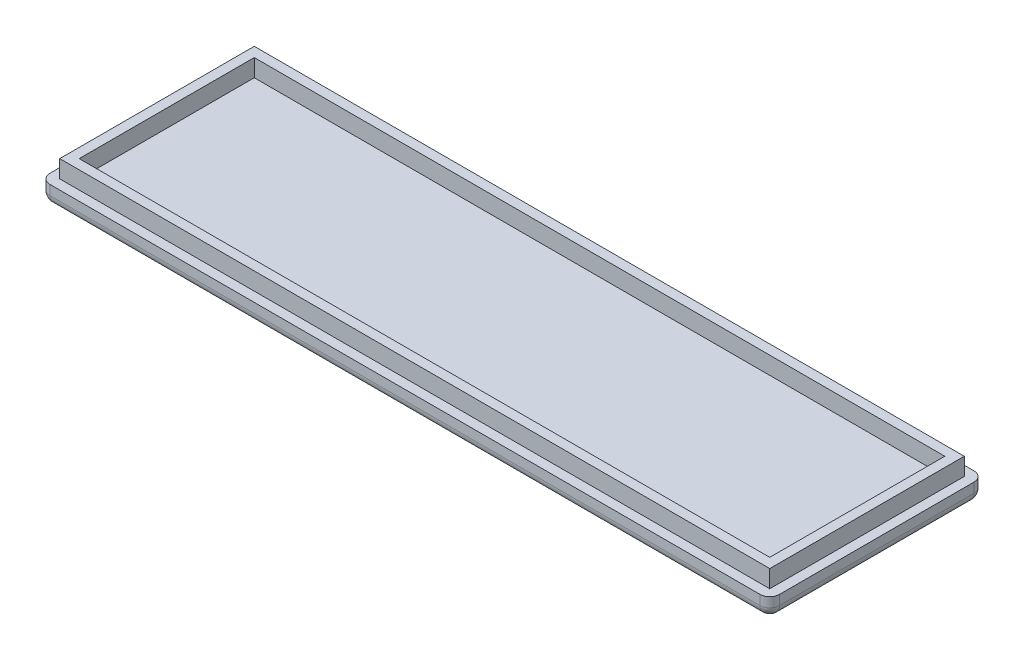
SolidWorks part; units mm, degrees
ref_plane "Front Plane" through (0, 0, 0) normal (0, 0, 1) x (1, 0, 0)
ref_plane "Top Plane" through (0, 0, 0) normal (0, 1, 0) x (1, 0, 0)
ref_plane "Right Plane" through (0, 0, 0) normal (1, 0, 0) x (0, 0, -1)
sketch "Sketch1" plane through (0, 0, 0) normal (0, 1, 0) x (1, 0, 0)
  line L1 (-37.5, -11) -> (37.5, -11)
  line L2 (-37.5, -11) -> (-37.5, 11)
  line L3 (-37.5, 11) -> (37.5, 11)
  line L4 (37.5, -11) -> (37.5, 11)
  line L5 (-37.5, -11) -> (37.5, 11) construction
  line L6 (-37.5, 11) -> (37.5, -11) construction
  point P0 (0, 0)
  dimension "D1" = 75
  dimension "D2" = 22
extrude "Boss-Extrude1" add sketch "Sketch1" along normal blind 2
sketch "Sketch2" plane through (0, 2, 0) normal (0, 1, 0) x (1, 0, 0)
  line L1 (-35.5, -9) -> (35.5, -9)
  line L2 (-35.5, -9) -> (-35.5, 9)
  line L3 (-35.5, 9) -> (35.5, 9)
  line L4 (35.5, -9) -> (35.5, 9)
  line L5 (-35.5, -9) -> (35.5, 9) construction
  line L6 (-35.5, 9) -> (35.5, -9) construction
  line L7 (-36.5, -10) -> (36.5, -10)
  line L8 (-36.5, -10) -> (-36.5, 10)
  line L9 (-36.5, 10) -> (36.5, 10)
  line L10 (36.5, -10) -> (36.5, 10)
  line L11 (-36.5, -10) -> (36.5, 10) construction
  line L12 (-36.5, 10) -> (36.5, -10) construction
  point P0 (0, 0)
  point P6 (0, 0)
  dimension "D1" = 71
  dimension "D2" = 18
  dimension "D3" = 73
  dimension "D4" = 20
extrude "Boss-Extrude2" add sketch "Sketch2" along normal blind 1.8
fillet "Fillet2" radius 1 8 edges at (0, 0, -11) (-37.5, 0, 0) (0, 0, 11) (37.5, 0, 0) (37.5, 1, 11) (37.5, 1, -11) (-37.5, 1, -11) (-37.5, 1, 11)
